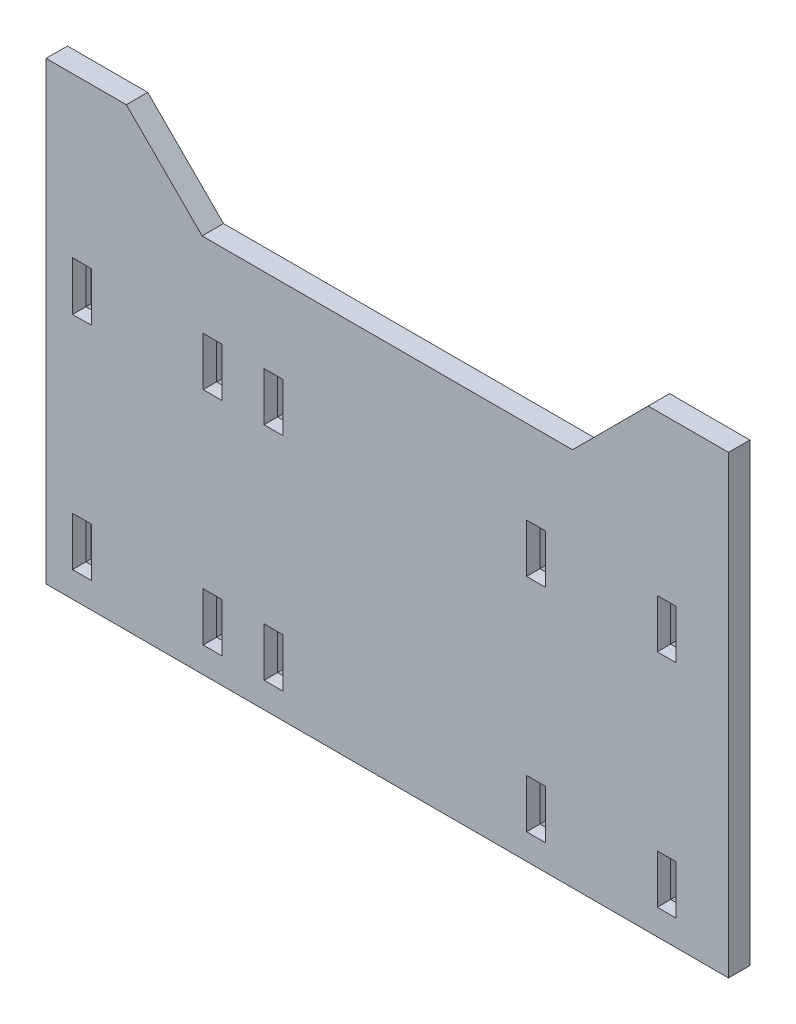
SolidWorks part; units mm, degrees
ref_plane "Front Plane" through (0, 0, 0) normal (0, 0, 1) x (1, 0, 0)
ref_plane "Top Plane" through (0, 0, 0) normal (0, 1, 0) x (1, 0, 0)
ref_plane "Right Plane" through (0, 0, 0) normal (1, 0, 0) x (0, 0, -1)
sketch "Sketch1" plane through (0, 0, 0) normal (0, 0, 1) x (1, 0, 0)
  line L6 (-34.3851, 25.207) -> (-30.8551, 25.207)
  line L7 (26.0149, 25.207) -> (29.5449, 25.207)
  line L8 (26.0149, 25.207) -> (26.0149, 16.093)
  line L9 (26.0149, 16.093) -> (29.5449, 16.093)
  line L10 (29.5449, 25.207) -> (29.5449, 16.093)
  line L12 (26.0149, -16.093) -> (29.5449, -16.093)
  line L13 (26.0149, -25.207) -> (26.0149, -16.093)
  line L14 (29.5449, -25.207) -> (29.5449, -16.093)
  line L15 (26.0149, -25.207) -> (29.5449, -25.207)
  line L16 (-19.4551, 25.207) -> (-22.9851, 25.1844)
  line L17 (-19.4551, 25.207) -> (-19.4406, 16.093)
  line L18 (-22.9851, 25.1844) -> (-22.9996, 16.1156)
  line L19 (-19.4406, 16.093) -> (-22.9996, 16.1156)
  line L20 (-19.4551, -16.093) -> (-22.9851, -16.093)
  line L21 (-19.4551, -25.207) -> (-19.4551, -16.093)
  line L22 (-22.9851, -25.207) -> (-22.9851, -16.093)
  line L23 (-19.4551, -25.207) -> (-22.9851, -25.207)
  line L39 (50.4149, 25.207) -> (53.9449, 25.207)
  line L40 (50.4149, 25.207) -> (50.4149, 16.093)
  line L41 (50.4149, 16.093) -> (53.9449, 16.093)
  line L42 (53.9449, 25.207) -> (53.9449, 16.093)
  line L43 (50.4149, -16.093) -> (53.9449, -16.093)
  line L44 (50.4149, -16.093) -> (50.4149, -25.207)
  line L45 (50.4149, -25.207) -> (53.9449, -25.207)
  line L46 (53.9449, -16.093) -> (53.9449, -25.207)
  line L47 (-34.3851, 25.207) -> (-34.3851, 16.093)
  line L48 (-34.3851, 16.093) -> (-30.8551, 16.093)
  line L49 (-30.8551, 25.207) -> (-30.8551, 16.093)
  line L50 (-34.3851, -16.093) -> (-30.8551, -16.093)
  line L51 (-34.3851, -16.093) -> (-34.3851, -25.207)
  line L52 (-34.3851, -25.207) -> (-30.8551, -25.207)
  line L53 (-30.8551, -16.093) -> (-30.8551, -25.207)
  line L60 (-58.785, 25.25) -> (-55.2552, 25.207)
  line L61 (-58.785, 25.25) -> (-58.785, 16.05)
  line L62 (-58.785, 16.05) -> (-55.2552, 16.093)
  line L63 (-55.2552, 25.207) -> (-55.2552, 16.093)
  line L64 (-58.7851, -16.093) -> (-55.2551, -16.093)
  line L65 (-58.7851, -16.093) -> (-58.7851, -25.207)
  line L66 (-58.7851, -25.207) -> (-55.2551, -25.207)
  line L67 (-55.2551, -16.093) -> (-55.2551, -25.207)
  line L80 (-63.7201, 30) -> (63.7201, 30)
  line L81 (63.7201, 30) -> (63.7201, -30)
  line L82 (52.1799, 25.207) -> (52.1799, 16.093) construction
  line L83 (27.7799, 16.093) -> (27.7799, 25.207) construction
  line L84 (-63.7201, 30) -> (-63.7201, -30)
  line L85 (-63.7201, -30) -> (63.7201, -30)
  line L87 (53.2799, 20.65) -> (50.4149, 20.65) construction
  line L88 (29.5449, 20.65) -> (26.0149, 20.65) construction
  line L89 (53.9449, -20.65) -> (50.4149, -20.65) construction
  line L90 (52.1799, -16.093) -> (52.1799, -25.207) construction
  line L91 (27.7799, -16.093) -> (27.7799, -25.207) construction
  line L92 (29.5449, -20.65) -> (26.0149, -20.65) construction
  line L93 (-19.4551, -20.65) -> (-22.9851, -20.65) construction
  line L94 (-21.2201, -16.093) -> (-21.2201, -25.207) construction
  line L95 (-32.6201, -16.093) -> (-32.6201, -25.207) construction
  line L96 (-30.8551, -20.65) -> (-34.3851, -20.65) construction
  line L97 (-55.2551, -20.65) -> (-58.7851, -20.65) construction
  line L98 (-57.0201, -16.093) -> (-57.0201, -25.207) construction
  line L99 (-57.0201, 25.2285) -> (-57.0201, 16.0715) construction
  line L100 (-32.6201, 25.207) -> (-32.6201, 16.093) construction
  line L101 (-21.2201, 25.1957) -> (-21.2201, 16.1043) construction
  line L102 (-55.2552, 20.65) -> (-58.785, 20.65) construction
  line L103 (-34.3851, 20.65) -> (-30.8551, 20.65) construction
  line L104 (-19.4479, 20.65) -> (-22.9923, 20.65) construction
  point P0 (0, 0)
  point P86 (0, 30)
  point P87 (63.7201, 0)
  dimension "D1" = 9.2
  dimension "D2" = 3.53
  dimension "D3" = 127.4402
  dimension "D4" = 60
  dimension "D7" = 11.4
  dimension "D8" = 24.4
  dimension "D5" = 27.7799
  dimension "D6" = 21.2201
  dimension "D10" = 20.65
  dimension "D11" = 20.65
  dimension "D9" = 24.4
extrude "Boss-Extrude1" add sketch "Sketch1" against normal blind 4
sketch "Sketch2" plane through (0, 0, 0) normal (0, 0, 1) x (1, 0, 0)
  line L0 (-63.7201, 30) -> (-63.7201, 55)
  line L1 (-63.7201, 55) -> (-48.7201, 55)
  line L2 (-48.7201, 55) -> (-34.578, 40.8579)
  line L7 (63.7201, 30) -> (-63.7201, 30)
  line L8 (48.7201, 55) -> (63.7201, 55)
  line L9 (63.7201, 55) -> (63.7201, 30)
  line L10 (48.7201, 55) -> (34.578, 40.8579)
  line L11 (34.578, 40.8579) -> (-34.578, 40.8579)
  line L12 (-63.7201, 30) -> (-63.7201, -30) construction
  line L14 (63.7201, -30) -> (63.7201, 30) construction
  dimension "D1" = 25
  dimension "D2" = 15
  dimension "D3" = 135
  dimension "D4" = 20
extrude "Boss-Extrude2" add sketch "Sketch2" against normal blind 4
chamfer "Chamfer1" distance 1.5 distance2 0.5 40 edges at (27.7799, 16.093, -4) (29.5449, 20.65, -4) (26.0149, 20.65, -4) (27.7799, 25.207, -4) (53.9449, 20.65, -4) (52.1799, 16.093, -4) (50.4149, 20.65, -4) (52.1799, 25.207, -4) (52.1799, -25.207, -4) (53.9449, -20.65, -4) (52.1799, -16.093, -4) (50.4149, -20.65, -4) (29.5449, -20.65, -4) (27.7799, -25.207, -4) (26.0149, -20.65, -4) (27.7799, -16.093, -4) (-21.2201, -25.207, -4) (-19.4551, -20.65, -4) (-21.2201, -16.093, -4) (-22.9851, -20.65, -4) (-30.8551, -20.65, -4) (-32.6201, -25.207, -4) (-34.3851, -20.65, -4) (-32.6201, -16.093, -4) (-55.2551, -20.65, -4) (-57.0201, -16.093, -4) (-58.7851, -20.65, -4) (-57.0201, -25.207, -4) (-21.2201, 25.1957, -4) (-19.4479, 20.65, -4) (-21.2201, 16.1043, -4) (-22.9923, 20.65, -4) (-32.6201, 16.093, -4) (-30.8551, 20.65, -4) (-32.6201, 25.207, -4) (-34.3851, 20.65, -4) (-57.0201, 16.0715, -4) (-55.2552, 20.65, -4) (-57.0201, 25.2285, -4) (-58.785, 20.65, -4)
equation "\"pin_hole_height\"=9.2"
equation "\"D1@Sketch1\"=\"pin_hole_height\""
equation "\"pin_hole_width\"=3.53"
equation "\"D2@Sketch1\"=\"pin_hole_width\""
